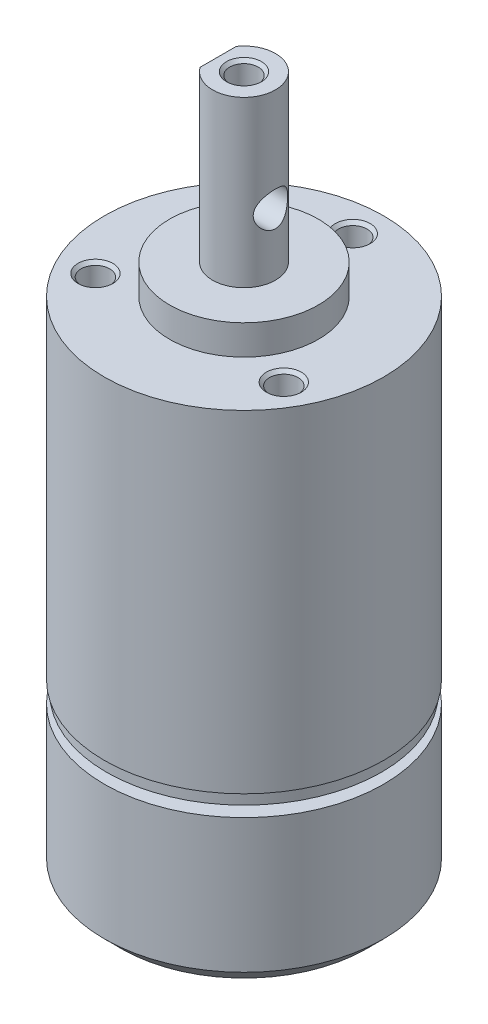
SolidWorks part; units mm, degrees
ref_plane "Front" through (0, 0, 0) normal (0, 0, 1) x (1, 0, 0)
ref_plane "Top" through (0, 0, 0) normal (0, 1, 0) x (1, 0, 0)
ref_plane "Right" through (0, 0, 0) normal (1, 0, 0) x (0, 0, -1)
sketch "草图1" plane through (0, 0, 0) normal (0, 0, 1) x (1, 0, 0)
  line L0 (3, 0) -> (12, 0)
  line L1 (12, 0) -> (12, 1)
  line L2 (12, 1) -> (12.2, 1)
  line L3 (12.2, 1) -> (12.2, 30)
  line L4 (12.2, 30) -> (6.5, 30)
  line L5 (6.5, 30) -> (6.5, 32.6)
  line L6 (6.5, 32.6) -> (0, 32.6)
  line L7 (0, 32.6) -> (0, -14)
  line L8 (0, 32.6) -> (0, -14) construction
  line L9 (3, 0) -> (3, -0.8)
  line L10 (3, -0.8) -> (12.2, -0.8)
  line L11 (12.2, -0.8) -> (12.2, -14)
  line L12 (12.2, -14) -> (0, -14)
  dimension "D1" = 12.2
  dimension "D2" = 2.6
  dimension "D3" = 1
  dimension "D4" = 12
  dimension "D5" = 30
  dimension "D6" = 6.5
  dimension "D7" = 44
  dimension "D8" = 3
  dimension "D9" = 13.2
revolve "旋转1" add sketch "草图1" angle 360 about L7
sketch "草图2" plane through (0, 32.6, 0) normal (0, 1, 0) x (1, 0, 0)
  circle A0 centre (0, 0) radius 2.75
  dimension "D1" = 5.5
extrude "凸台-拉伸1" add sketch "草图2" along normal blind 14.4
sketch "草图3" plane through (0, 0, 0) normal (0, 0, 1) x (1, 0, 0)
  line L0 (0, 47) -> (0, 0) construction
  line L1 (2.75, 47) -> (-2.75, 47) construction
  line L2 (-2.75, 47) -> (-2.75, 32.6) construction
  line L3 (-3.75, 47.5) -> (-2.25, 47.5)
  line L4 (-3.75, 47.5) -> (-3.75, 35.5)
  line L5 (-3.75, 35.5) -> (-2.25, 35.5)
  line L6 (-2.25, 47.5) -> (-2.25, 35.5)
  dimension "D1" = 0.5
  dimension "D2" = 0.5
  dimension "D3" = 11.5
  dimension "D4" = 1.5
extrude "切除-拉伸1" cut sketch "草图3" against normal through all both and the other way through all
sketch "草图4" plane through (-2.25, 0, 0) normal (-1, 0, 0) x (0, 0, 1)
  line L0 (0, 47) -> (0, 38) construction
  line L1 (1.5811, 47) -> (-1.5811, 47) construction
  circle A0 centre (0, 38) radius 1.5
  dimension "D2" = 3
  dimension "D1" = 9
extrude "切除-拉伸2" cut sketch "草图4" against normal up to next
sketch "草图5" plane through (0, 47, 0) normal (0, 1, 0) x (1, 0, 0)
  point P0 (0, 0)
hole_wizard "M3 螺纹孔1" positions "3D草图1" profile "草图6" tap size "M3" standard "GB"
sketch3d "3D草图1"
  point P0 (0, 47, 0)
sketch "草图6" plane through (0, 47, 0) normal (1, 0, 0) x (0, 0, 1)
  line L0 (0, 0) -> (0, 6.2511)
  line L1 (0, 6.2511) -> (1.25, 5.5)
  line L2 (1.25, 5.5) -> (1.25, 0.275)
  line L3 (1.25, 0.275) -> (1.525, 0)
  line L5 (1.525, 0) -> (0, 0)
  line L6 (-1.25, 0.275) -> (-1.525, 0) construction
  line L10 (0, 6.2511) -> (-1.25, 5.5) construction
  line L11 (0, -6.35) -> (0, 107.95) construction
  dimension "螺纹孔钻头直径" = 2.5
  dimension "螺纹孔钻头深度" = 5.5
  dimension "近端锥形沉头孔直径" = 3.05
  dimension "近端锥形沉头孔角度" = 90
  dimension "导头角度" = 118
cosmetic thread "孔螺蚊线1" parameters "D1"=5.5, "D2"=3
sketch "草图7" plane through (0, 30, 0) normal (0, 1, 0) x (1, 0, 0)
  line L0 (0, 0) -> (0, 9.5) construction
  line L1 (0, 0) -> (-8.2272, -4.75) construction
  line L2 (0, 0) -> (8.2272, -4.75) construction
  circle A0 centre (0, 0) radius 9.5 construction
  dimension "D1" = 19
  dimension "D2" = 120
  dimension "D3" = 120
hole_wizard "M3 螺纹孔2" positions "3D草图2" profile "草图8" tap size "M3" standard "GB"
sketch3d "3D草图2"
  point P0 (8.2272, 30, 4.75)
  point P3 (-8.2272, 30, 4.75)
  point P6 (0, 30, -9.5)
sketch "草图8" plane through (8.2272, 30, 4.75) normal (1, 0, 0) x (0, 0, 1)
  line L0 (0, 0) -> (0, 4.7511)
  line L1 (0, 4.7511) -> (1.25, 4)
  line L2 (1.25, 4) -> (1.25, 0.275)
  line L3 (1.25, 0.275) -> (1.525, 0)
  line L5 (1.525, 0) -> (0, 0)
  line L6 (-1.25, 0.275) -> (-1.525, 0) construction
  line L10 (0, 4.7511) -> (-1.25, 4) construction
  line L11 (0, -6.35) -> (0, 107.95) construction
  dimension "螺纹孔钻头直径" = 2.5
  dimension "螺纹孔钻头深度" = 4
  dimension "近端锥形沉头孔直径" = 3.05
  dimension "近端锥形沉头孔角度" = 90
  dimension "导头角度" = 118
cosmetic thread "孔螺蚊线5" parameters "D1"=4, "D2"=3
cosmetic thread "孔螺蚊线6" parameters "D1"=4, "D2"=3
cosmetic thread "孔螺蚊线7" parameters "D1"=4, "D2"=3
chamfer "倒角1" distance 1.5 angle 45 1 edges at (-12.2, -14, 0)
sketch "草图9" plane through (0, -14, 0) normal (0, -1, 0) x (1, 0, 0)
  circle A0 centre (0, 0) radius 3
  dimension "D1" = 6
extrude "凸台-拉伸2" add sketch "草图9" along normal blind 4
